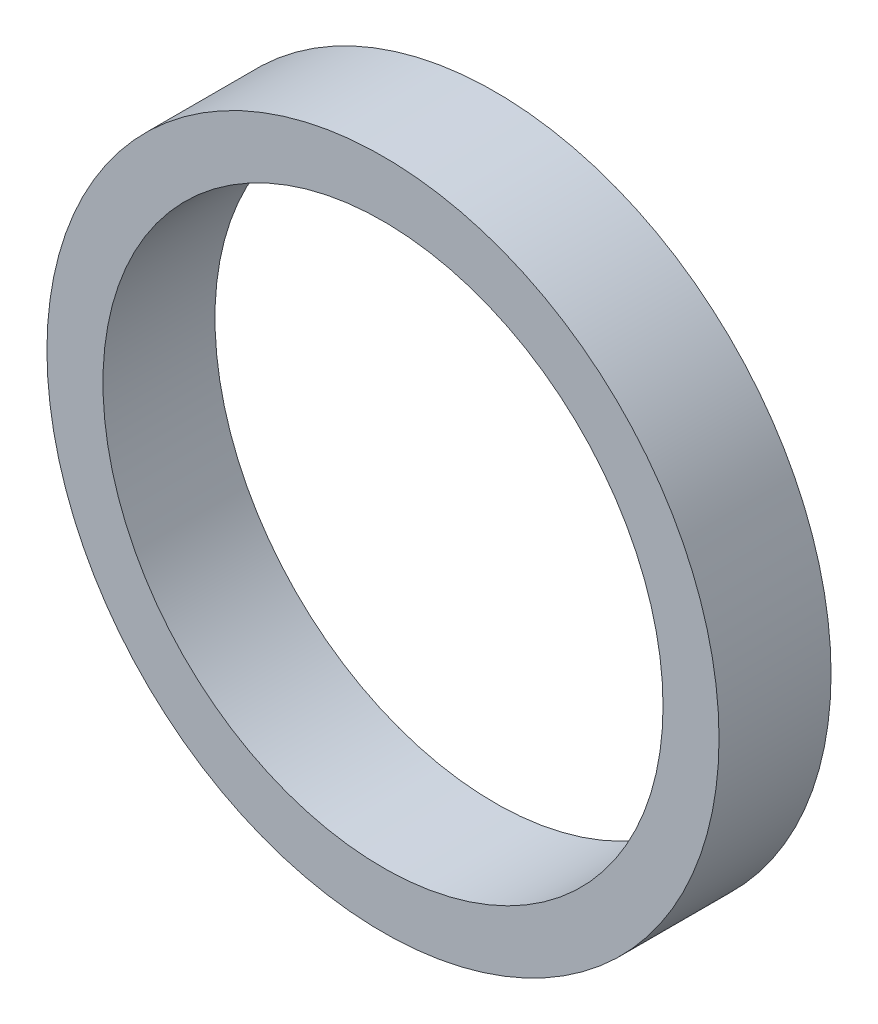
SolidWorks part; units mm, degrees
material "6061 合金"
ref_plane "前视基准面" through (0, 0, 0) normal (0, 0, 1) x (1, 0, 0)
ref_plane "上视基准面" through (0, 0, 0) normal (0, 1, 0) x (1, 0, 0)
ref_plane "右视基准面" through (0, 0, 0) normal (1, 0, 0) x (0, 0, -1)
other "Configuration Table"
sketch "草图1" plane through (0, 0, 0) normal (0, 0, 1) x (1, 0, 0)
  circle A0 centre (0, 0) radius 5
  circle A1 centre (0, 0) radius 6
  dimension "D1" = 10
  dimension "D2" = 12
extrude "凸台-拉伸1" add sketch "草图1" along normal blind 2 contours A0 | A1
sketch "草图2" plane through (0, 0, 0) normal (0, 0, -1) x (-1, 0, 0)
  circle A0 centre (0, 0) radius 6
  circle A1 centre (0, 0) radius 5 construction
  circle A2 centre (0, 0) radius 5
  dimension "D1" = 12
extrude "凸台-拉伸2" [suppressed] add sketch "草图2" against normal blind 1
sketch "草图3" [suppressed] plane through (0, 0, 15) normal (0, 0, 1) x (1, 0, 0)
  circle A1 centre (0, 0) radius 5 construction
  circle A2 centre (0, 0) radius 5
  circle A3 centre (0, 0) radius 7 construction
  circle A4 centre (0, 0) radius 7
extrude "凸台-拉伸3" [suppressed] add sketch "草图3" against normal blind 1
fillet "圆角1" [suppressed] radius 0.5
chamfer "倒角1" [suppressed] distance 0.5 angle 45
